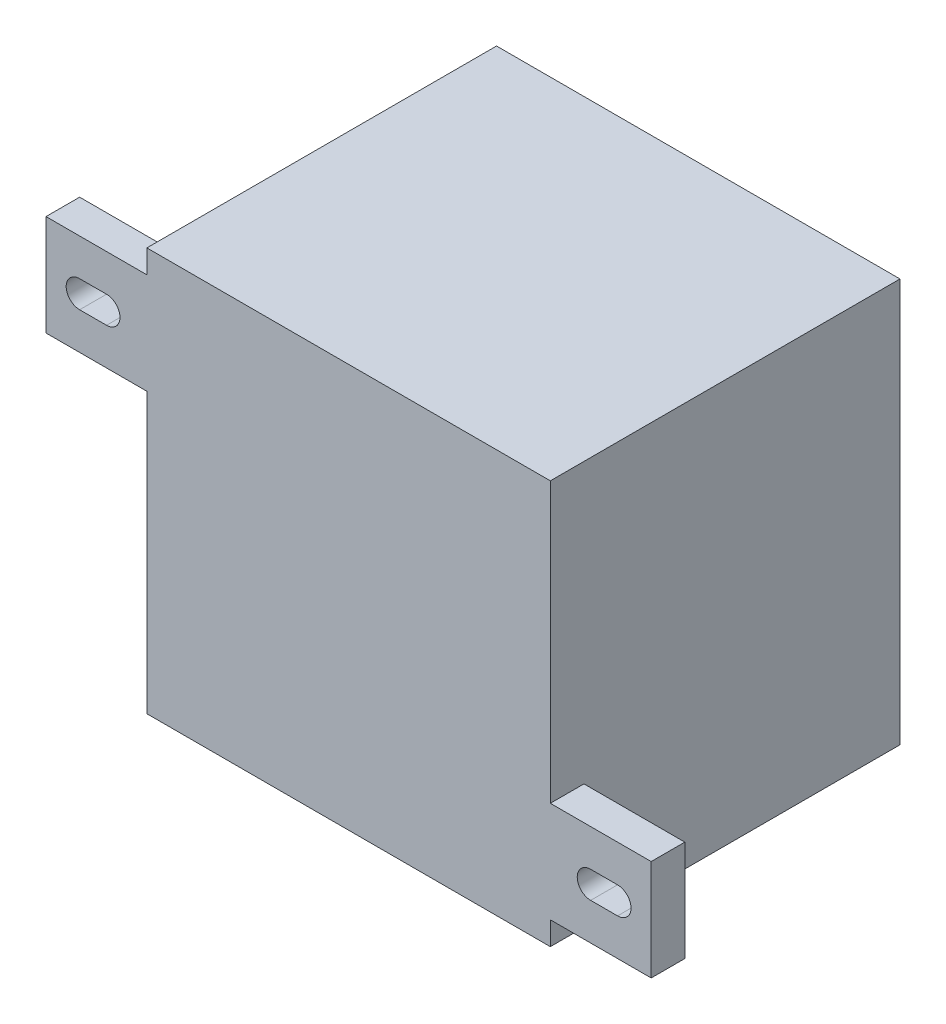
SolidWorks part; units mm, degrees
ref_plane "前视基准面" through (0, 0, 0) normal (0, 0, 1) x (1, 0, 0)
ref_plane "上视基准面" through (0, 0, 0) normal (0, 1, 0) x (1, 0, 0)
ref_plane "右视基准面" through (0, 0, 0) normal (1, 0, 0) x (0, 0, -1)
sketch "草图1" plane through (0, 0, 0) normal (0, 0, 1) x (1, 0, 0)
  line L1 (30, -30) -> (-30, -30)
  line L2 (30, -30) -> (30, 30)
  line L3 (30, 30) -> (-30, 30)
  line L4 (-30, -30) -> (-30, 30)
  line L5 (30, -30) -> (-30, 30) construction
  line L6 (30, 30) -> (-30, -30) construction
  point P0 (0, 0)
  dimension "D1" = 60
  dimension "D2" = 60
extrude "凸台-拉伸1" add sketch "草图1" along normal blind 52
sketch "草图2" plane through (0, 0, 52) normal (0, 0, 1) x (1, 0, 0)
  line L0 (-30, 30) -> (-30, -30) construction
  line L1 (-30, 26.5329) -> (-45, 26.5329)
  line L2 (-30, 26.5329) -> (-30, 11.5329)
  line L3 (-30, 11.5329) -> (-45, 11.5329)
  line L4 (-45, 26.5329) -> (-45, 11.5329)
  line L5 (-45, 19.0329) -> (-30, 19.0329) construction
  line L6 (-40, 19.0329) -> (-36, 19.0329) construction
  line L7 (-40, 21.0329) -> (-36, 21.0329)
  line L8 (-40, 17.0329) -> (-36, 17.0329)
  line L9 (30, -26.5329) -> (45, -26.5329)
  line L10 (30, -26.5329) -> (30, -11.5329)
  line L11 (30, -11.5329) -> (45, -11.5329)
  line L12 (45, -26.5329) -> (45, -11.5329)
  line L13 (45, -19.0329) -> (30, -19.0329) construction
  line L14 (40, -19.0329) -> (36, -19.0329) construction
  line L15 (40, -21.0329) -> (36, -21.0329)
  line L16 (40, -17.0329) -> (36, -17.0329)
  arc A0 (-40, 21.0329) -> (-40, 17.0329) centre (-40, 19.0329) ccw
  arc A1 (-36, 17.0329) -> (-36, 21.0329) centre (-36, 19.0329) ccw
  arc A2 (40, -21.0329) -> (40, -17.0329) centre (40, -19.0329) ccw
  arc A3 (36, -17.0329) -> (36, -21.0329) centre (36, -19.0329) ccw
  point P10 (-38, 19.0329)
  point P25 (38, -19.0329)
  point P30 (0, 0)
  dimension "D1" = 2
  dimension "D2" = 4
  dimension "D3" = 15
  dimension "D4" = 15
  dimension "D5" = 5
  dimension "D7" = 85
  dimension "D6" = 2
extrude "凸台-拉伸2" add sketch "草图2" against normal blind 5
